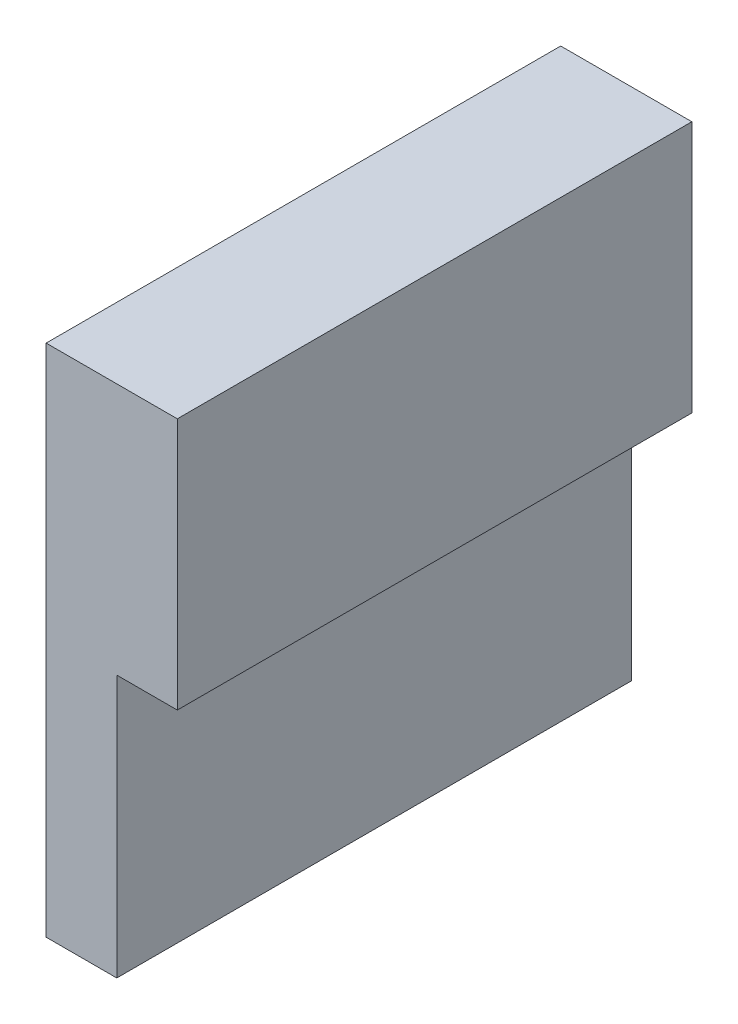
SolidWorks part; units mm, degrees
ref_plane "Front Plane" through (0, 0, 0) normal (0, 0, 1) x (1, 0, 0)
ref_plane "Top Plane" through (0, 0, 0) normal (0, 1, 0) x (1, 0, 0)
ref_plane "Right Plane" through (0, 0, 0) normal (1, 0, 0) x (0, 0, -1)
sketch "Sketch1" plane through (0, 0, 0) normal (1, 0, 0) x (0, 0, -1)
  line L1 (0, 0) -> (-51, 0)
  line L2 (0, 0) -> (0, -51)
  line L3 (0, -51) -> (-51, -51)
  line L4 (-51, 0) -> (-51, -51)
  dimension "D1" = 51
  dimension "D2" = 51
extrude "Boss-Extrude1" add sketch "Sketch1" along normal blind 13
sketch "Sketch2" plane through (13, 0, 0) normal (1, 0, 0) x (0, 0, -1)
  line L0 (0, -51) -> (0, 0) construction
  line L1 (-51, -51) -> (0, -51)
  line L2 (-51, -51) -> (-51, -25)
  line L3 (-51, -25) -> (0, -25)
  line L4 (0, -51) -> (0, -25)
  line L5 (0, 0) -> (-51, 0) construction
  dimension "D1" = 25
extrude "Cut-Extrude1" cut sketch "Sketch2" against normal blind 6
